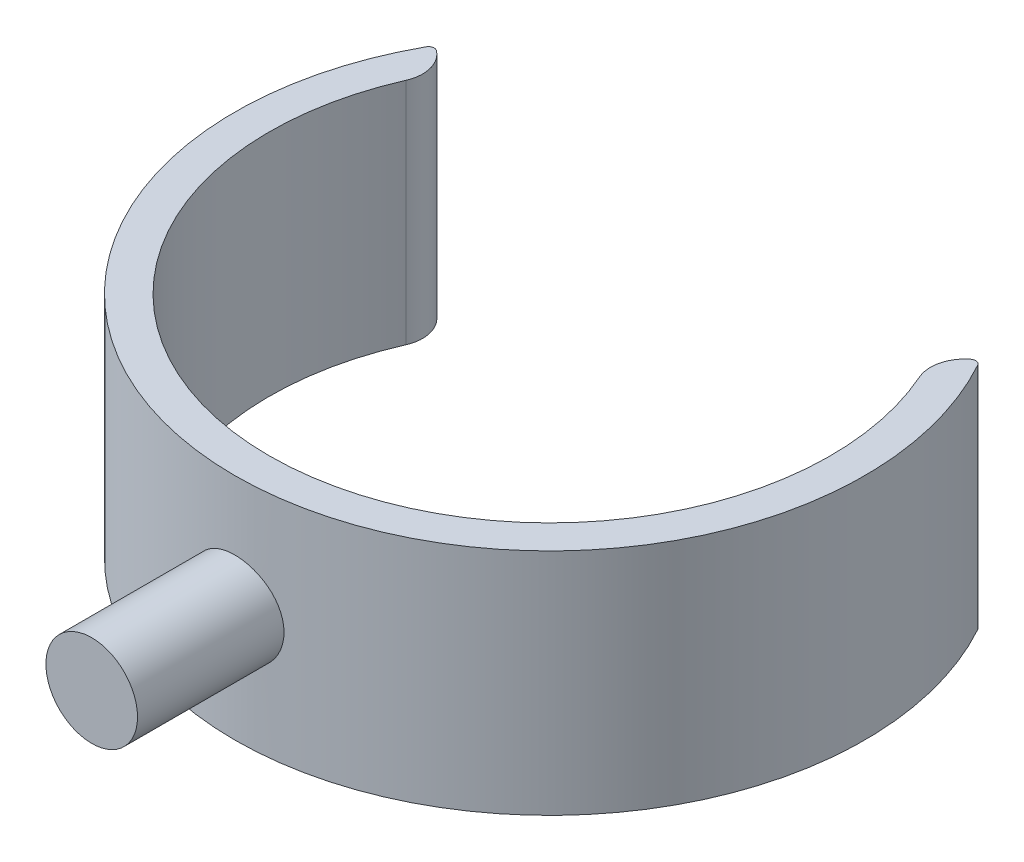
SolidWorks part; units mm, degrees
ref_plane "Alzado" through (0, 0, 0) normal (0, 0, 1) x (1, 0, 0)
ref_plane "Planta" through (0, 0, 0) normal (0, 1, 0) x (1, 0, 0)
ref_plane "Vista lateral" through (0, 0, 0) normal (1, 0, 0) x (0, 0, -1)
sketch "Croquis1" plane through (0, 0, 0) normal (0, 1, 0) x (1, 0, 0)
  line L0 (0, 0) -> (0, 40) construction
  line L1 (0, 0) -> (23.8157, 13.75)
  line L2 (0, 0) -> (-23.8157, 13.75)
  arc A0 (-23.8157, 13.75) -> (23.8157, 13.75) centre (0, 0) ccw
  arc A1 (-21.2176, 12.25) -> (21.2176, 12.25) centre (0, 0) ccw
  circle A3 centre (0, 0) radius 24.5 construction
  circle A4 centre (0, 0) radius 27.5 construction
  point P3 (38.2522, 11.6949)
  point P8 (37, 0)
  dimension "D1" = 55
  dimension "D3" = 60
  dimension "D2" = 3
extrude "Extruir1" add sketch "Croquis1" along normal blind 20 contours A1 L2 A0 L1
sketch "Croquis2" plane through (0, 0, 0) normal (0, 0, 1) x (1, 0, 0)
  line L0 (0, 0) -> (0, 20) construction
  line L1 (27.5, 20) -> (-27.5, 20) construction
  circle A0 centre (0, 10) radius 4
  dimension "D1" = 8
extrude "Extruir2" add sketch "Croquis2" against normal up to surface (12.7925 mm away) from offset 40
fillet "Redondeo1" radius 3 2 edges at (-21.2176, 10, -12.25) (21.2176, 10, -12.25)
fillet "Redondeo2" radius 0.5 2 edges at (23.8157, 10, -13.75) (-23.8157, 10, -13.75)
